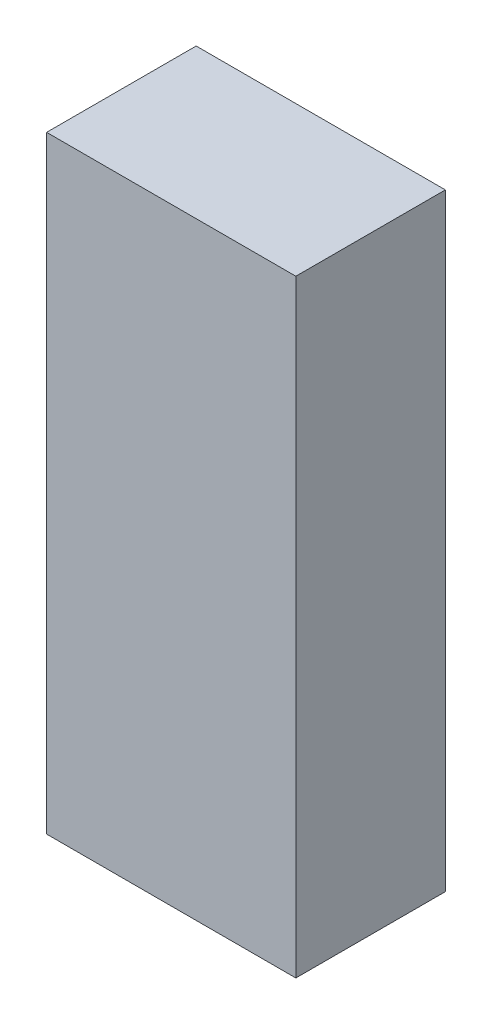
SolidWorks part; units mm, degrees
ref_plane "Front Plane" through (0, 0, 0) normal (0, 0, 1) x (1, 0, 0)
ref_plane "Top Plane" through (0, 0, 0) normal (0, 1, 0) x (1, 0, 0)
ref_plane "Right Plane" through (0, 0, 0) normal (1, 0, 0) x (0, 0, -1)
sketch "Sketch1" plane through (0, 0, 0) normal (0, 0, 1) x (1, 0, 0)
  line L1 (-7.75, -18.9) -> (7.75, -18.9)
  line L2 (-7.75, -18.9) -> (-7.75, 18.9)
  line L3 (-7.75, 18.9) -> (7.75, 18.9)
  line L4 (7.75, -18.9) -> (7.75, 18.9)
  line L5 (-7.75, -18.9) -> (7.75, 18.9) construction
  line L6 (-7.75, 18.9) -> (7.75, -18.9) construction
  point P0 (0, 0)
extrude "Envelope" add sketch "Sketch1" along normal blind 9.3
